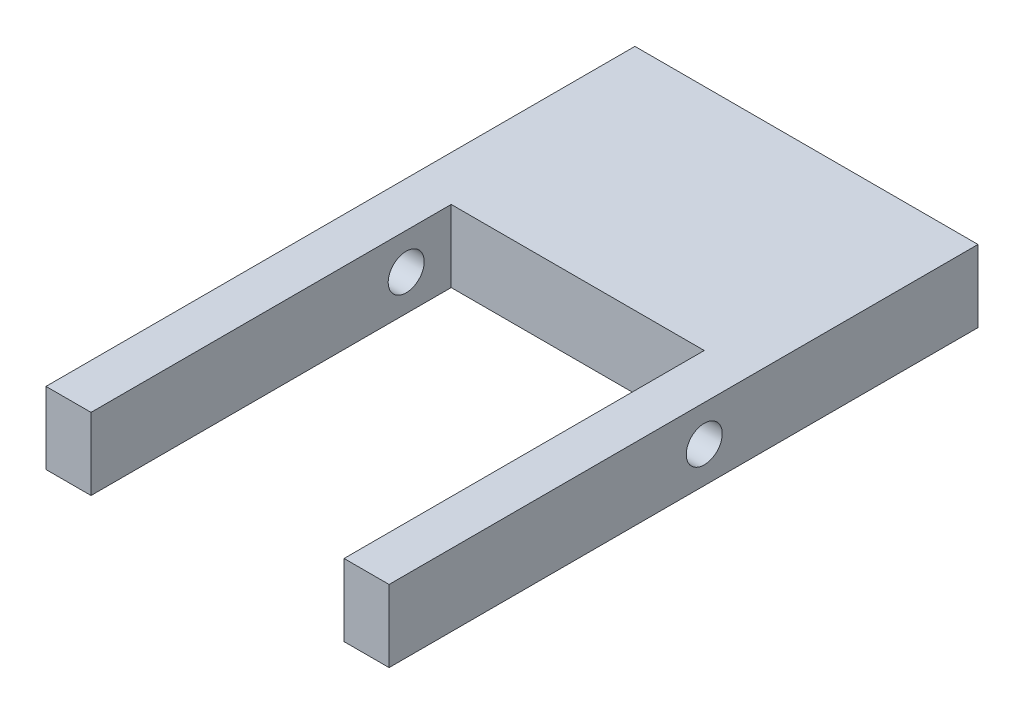
SolidWorks part; units mm, degrees
ref_plane "Front" through (0, 0, 0) normal (0, 0, 1) x (1, 0, 0)
ref_plane "Top" through (0, 0, 0) normal (0, 1, 0) x (1, 0, 0)
ref_plane "Right" through (0, 0, 0) normal (1, 0, 0) x (0, 0, -1)
sketch "Sketch1" plane through (0, 0, 0) normal (0, 1, 0) x (1, 0, 0)
  line L1 (0, 0) -> (38.1, 0)
  line L2 (0, 0) -> (0, 25.4)
  line L3 (0, 25.4) -> (38.1, 25.4)
  line L4 (38.1, 0) -> (38.1, 25.4)
  dimension "D1" = 38.1
  dimension "D2" = 25.4
extrude "Boss-Extrude1" add sketch "Sketch1" along normal blind 8
sketch "Sketch2" plane through (0, 0, 0) normal (0, 0, 1) x (1, 0, 0)
  line L0 (0, 8) -> (38.1, 8) construction
  line L1 (38.1, 0) -> (33.1, 0)
  line L2 (38.1, 0) -> (38.1, 8)
  line L3 (38.1, 8) -> (33.1, 8)
  line L4 (33.1, 0) -> (33.1, 8)
  dimension "D1" = 5
extrude "Boss-Extrude2" add sketch "Sketch2" along normal blind 40
sketch "Sketch3" plane through (33.1, 0, 0) normal (-1, 0, 0) x (0, 0, 1)
  line L0 (40, 4) -> (0, 4)
  line L1 (40, 8) -> (40, 0) construction
  line L2 (0, 8) -> (0, 0) construction
  circle A0 centre (5, 4) radius 2
  dimension "D1" = 5
extrude "Cut-Extrude1" cut sketch "Sketch3" against normal blind 30 contours A0
pattern_linear "LPattern1" count 2 spacing 33.1 along (-1, 0, 0) of "Boss-Extrude2", "Cut-Extrude1"
